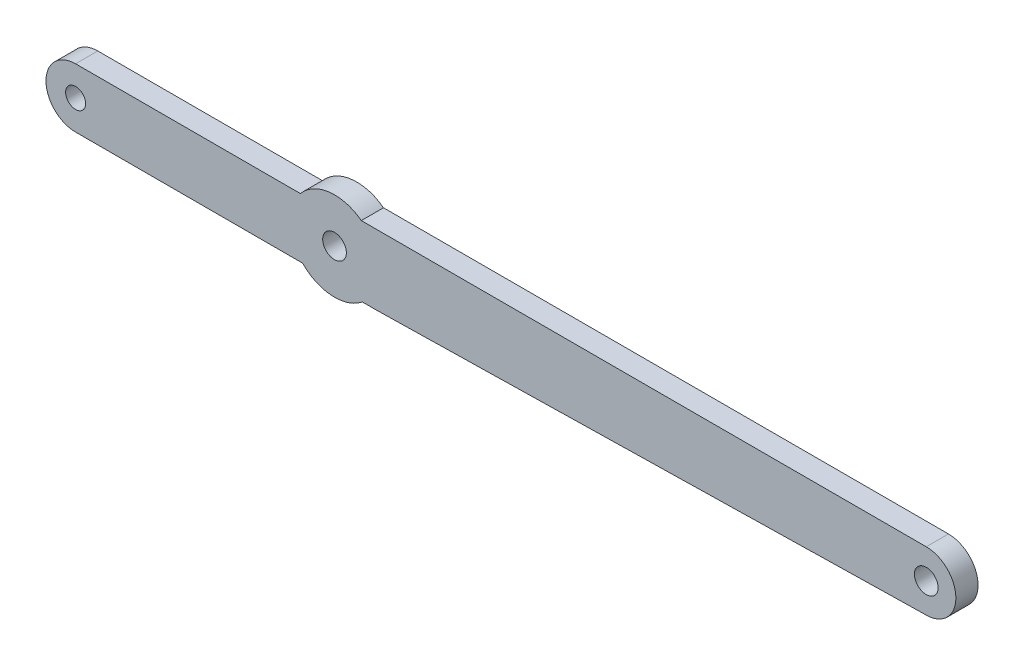
SolidWorks part; units mm, degrees
ref_plane "前视基准面" through (0, 0, 0) normal (0, 0, 1) x (1, 0, 0)
ref_plane "上视基准面" through (0, 0, 0) normal (0, 1, 0) x (1, 0, 0)
ref_plane "右视基准面" through (0, 0, 0) normal (1, 0, 0) x (0, 0, -1)
ref_plane "基准面4" through (0, 0, 3) normal (0, 0, 1) x (1, 0, 0)
sketch "草图1" plane through (0, 0, 3) normal (0, 0, 1) x (1, 0, 0)
  line L0 (-60.8325, 7.5141) -> (-91.2187, 7.5141)
  line L1 (-91.2187, -0.4859) -> (-60.5316, -0.4859)
  line L2 (-52.4516, -0.9904) -> (-50.421, -0.9904)
  line L3 (-50.421, -0.9904) -> (23.8166, 0.4678)
  line L4 (23.778, 8.4676) -> (-52.5964, 8.4676)
  line L5 (23.8166, 0.4678) -> (23.8566, 0.4686)
  arc A0 (-52.5964, 8.4676) -> (-60.8325, 7.5141) centre (-56.2156, 3.6821) ccw
  arc A1 (-91.2187, 7.5141) -> (-91.2187, -0.4859) centre (-91.2187, 3.5141) ccw
  arc A2 (-60.5316, -0.4859) -> (-52.4516, -0.9904) centre (-56.2156, 3.6821) ccw
  arc A3 (23.8566, 0.4686) -> (23.778, 8.4676) centre (23.778, 4.4677) ccw
extrude "凸台-拉伸1" add sketch "草图1" against normal blind 3
sketch "草图2" plane through (0, 0, 3) normal (0, 0, 1) x (1, 0, 0)
  circle A0 centre (23.778, 4.4676) radius 1.35
extrude "切除-拉伸1" cut sketch "草图2" against normal blind 2.4444
sketch "草图3" plane through (0, 0, 0) normal (0, 0, -1) x (-1, 0, 0)
  circle A0 centre (-23.778, 4.4678) radius 1.6
  circle A1 centre (56.2156, 3.6821) radius 1.6
  circle A2 centre (91.2187, 3.5141) radius 1.35
  dimension "D1" = 3.2
  dimension "D2" = 2.7
  dimension "D3" = 3.2
extrude "切除-拉伸3" cut sketch "草图3" against normal through all contours A0 | A1 | A2
